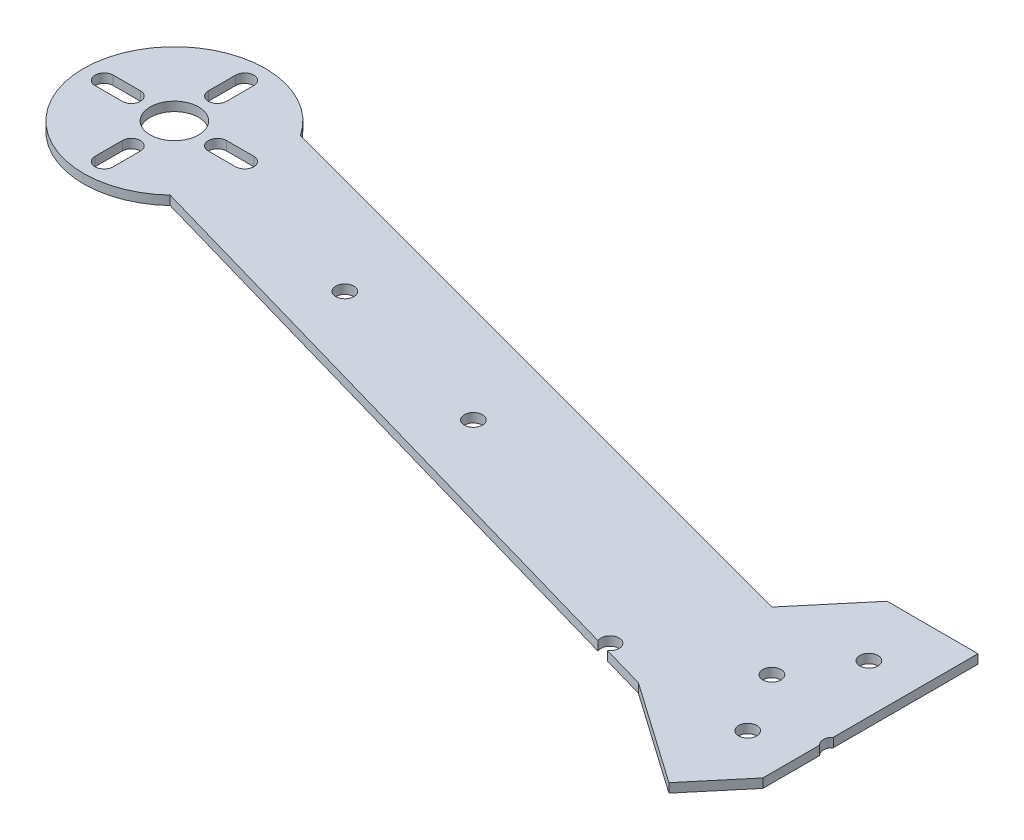
SolidWorks part; units mm, degrees
ref_plane "Front Plane" through (0, 0, 0) normal (0, 0, 1) x (1, 0, 0)
ref_plane "Top Plane" through (0, 0, 0) normal (0, 1, 0) x (1, 0, 0)
ref_plane "Right Plane" through (0, 0, 0) normal (1, 0, 0) x (0, 0, -1)
sketch "Sketch1" plane through (0, 0, 0) normal (0, 1, 0) x (1, 0, 0)
  line L7 (0, 0) -> (0, 35.5)
  line L8 (0, 35.5) -> (-15, 35.5)
  line L9 (-15, 35.5) -> (-23.6776, 25.1584)
  line L10 (-23.6776, 25.1584) -> (-129.9295, 53.6285)
  line L11 (0, 0) -> (-7.0707, -8.4265)
  line L12 (-7.0707, -8.4265) -> (-23.8633, 3.3318)
  line L17 (-23.8633, 3.3318) -> (-31.0343, 5.3877)
  line L20 (-23.8633, 3.3318) -> (-23.6776, 25.1584) construction
  line L21 (-142.4295, 45.3369) -> (-135.843, 45.3369) construction
  line L23 (-142.4295, 45.3369) -> (-142.4295, 51.2621) construction
  line L24 (-135.3295, 45.3369) -> (-130.8295, 45.3369) construction
  line L25 (-135.3295, 46.8369) -> (-130.8295, 46.8369)
  line L26 (-135.3295, 43.8369) -> (-130.8295, 43.8369)
  line L27 (-142.4295, 38.2369) -> (-142.4295, 33.7369) construction
  line L28 (-140.9295, 38.2369) -> (-140.9295, 33.7369)
  line L29 (-143.9295, 38.2369) -> (-143.9295, 33.7369)
  line L30 (-149.5295, 45.3369) -> (-154.0295, 45.3369) construction
  line L31 (-149.5295, 43.8369) -> (-154.0295, 43.8369)
  line L32 (-149.5295, 46.8369) -> (-154.0295, 46.8369)
  line L33 (-142.4295, 52.4369) -> (-142.4295, 56.9369) construction
  line L34 (-143.9295, 52.4369) -> (-143.9295, 56.9369)
  line L35 (-140.9295, 52.4369) -> (-140.9295, 56.9369)
  line L36 (-142.4295, 45.3369) -> (-23.7764, 13.5439) construction
  line L37 (-33.2238, 6.0154) -> (-132.1793, 34.3855)
  arc A14 (-129.9295, 53.6285) -> (-132.1793, 34.3855) centre (-142.4295, 45.3369) ccw
  circle A15 centre (-8, 25.5) radius 1.5
  circle A16 centre (-14, 15.5) radius 1.5
  circle A17 centre (-8, 5.5) radius 1.5
  arc A18 (-31.0343, 5.3877) -> (-33.2238, 6.0154) centre (-31.86, 6.64) ccw
  circle A19 centre (1, 10.5) radius 1.5
  circle A20 centre (-142.4295, 45.3369) radius 4
  arc A21 (-135.3295, 46.8369) -> (-135.3295, 43.8369) centre (-135.3295, 45.3369) ccw
  arc A22 (-130.8295, 43.8369) -> (-130.8295, 46.8369) centre (-130.8295, 45.3369) ccw
  arc A23 (-140.9295, 38.2369) -> (-143.9295, 38.2369) centre (-142.4295, 38.2369) ccw
  arc A24 (-143.9295, 33.7369) -> (-140.9295, 33.7369) centre (-142.4295, 33.7369) ccw
  arc A25 (-149.5295, 43.8369) -> (-149.5295, 46.8369) centre (-149.5295, 45.3369) ccw
  arc A26 (-154.0295, 46.8369) -> (-154.0295, 43.8369) centre (-154.0295, 45.3369) ccw
  arc A27 (-143.9295, 52.4369) -> (-140.9295, 52.4369) centre (-142.4295, 52.4369) ccw
  arc A28 (-140.9295, 56.9369) -> (-143.9295, 56.9369) centre (-142.4295, 56.9369) ccw
  circle A29 centre (-104.0146, 35.0437) radius 1.5
  circle A30 centre (-75.0368, 27.2791) radius 1.5
  point P20 (-7.5, 35.5)
  point P25 (-133.0795, 45.3369)
  point P35 (-142.4295, 35.9869)
  point P42 (-151.7795, 45.3369)
  point P49 (-142.4295, 54.6869)
  point P55 (-142.4295, 45.3369)
  dimension "D12" = 3
  dimension "D16" = 3
  dimension "D17" = 3
  dimension "D18" = 3
  dimension "D19" = 3
  dimension "D20" = 8
  dimension "D21" = 10
  dimension "D23" = 20
  dimension "D24" = 14
  dimension "D25" = 15
  dimension "D27" = 8
  dimension "D32" = 3
  dimension "D33" = 3
  dimension "D34" = 30
  dimension "D35" = 39.77
  dimension "D36" = 17.86
  dimension "D37" = 8.86
  dimension "D1" = 35.5
  dimension "D2" = 15
  dimension "D3" = 13.5
  dimension "D4" = 130
  dimension "D5" = 115
  dimension "D6" = 110
  dimension "D7" = 90
  dimension "D8" = 11
  dimension "D9" = 140
  dimension "D10" = 20.5
  dimension "D11" = 95
  dimension "D13" = 15
  dimension "D14" = 12.5
  dimension "D15" = 74.49
  dimension "D22" = 30
  dimension "D26" = 15
  dimension "D28" = 3
  dimension "D29" = 4.5
  dimension "D30" = 7.1
  dimension "D31" = 4
extrude "Boss-Extrude1" add sketch "Sketch1" along normal blind 1.5 contours A19 L7 L8 L9 L10 A14 L37 A18 L17 L12 L11 A30 A29 A28 L35 A27 L34 A26 L32 A25 L31 A24 L29 A23 L28 A22 L26 A21 L25 A20 A17 A16 A15
